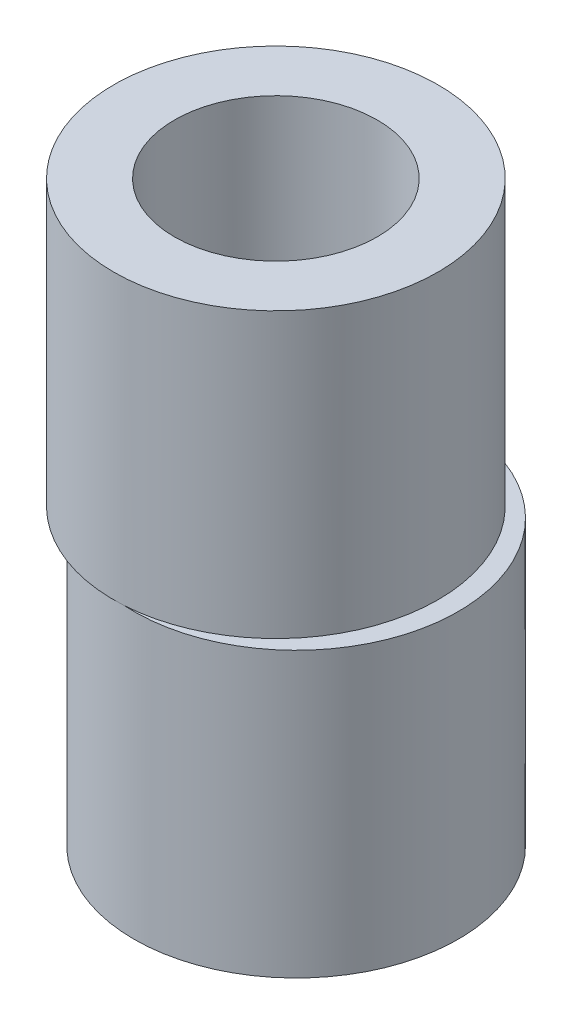
SolidWorks part; units mm, degrees
ref_plane "Front Plane" through (0, 0, 0) normal (0, 0, 1) x (1, 0, 0)
ref_plane "Top Plane" through (0, 0, 0) normal (0, 1, 0) x (1, 0, 0)
ref_plane "Right Plane" through (0, 0, 0) normal (1, 0, 0) x (0, 0, -1)
sketch "Sketch1" plane through (0, 0, 0) normal (0, 1, 0) x (1, 0, 0)
  line L0 (0, 0) -> (0.5, 0) construction
  circle A0 centre (0, 0) radius 4
  circle A1 centre (0.5, 0) radius 2.5
  dimension "D1" = 8
  dimension "D3" = 5
extrude "Boss-Extrude1" add sketch "Sketch1" along normal blind 7
sketch "Sketch2" plane through (0, 7, 0) normal (0, 1, 0) x (1, 0, 0)
  line L0 (0, 0) -> (-0.5, 0) construction
  circle A0 centre (-0.5, 0) radius 2.5
  circle A1 centre (-0.5, 0) radius 4
  dimension "D2" = 5
  dimension "D3" = 8
  dimension "D1" = 0.5
extrude "Boss-Extrude2" add sketch "Sketch2" along normal blind 7
equation "\"D2@Sketch1\"=\"eccentricity\""
equation "\"D1@Sketch2\"=\"eccentricity\""
